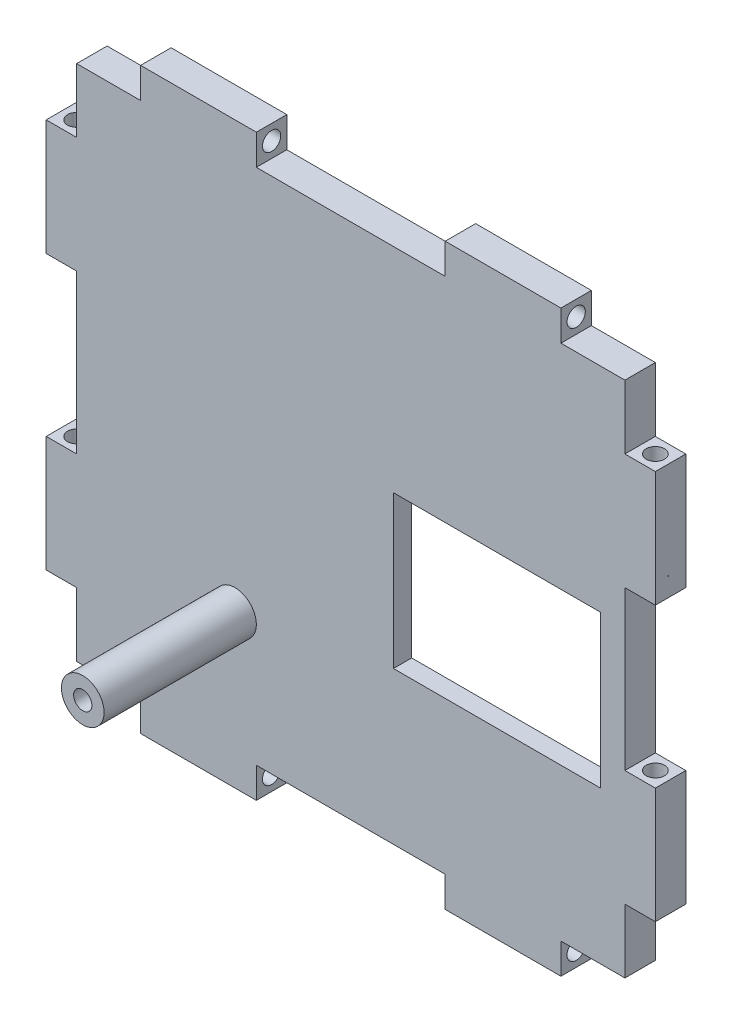
SolidWorks part; units mm, degrees
material "Alliage 1060"
ref_plane "Plan de dessus" through (0, 0, 0) normal (0, 0, 1) x (1, 0, 0)
ref_plane "Plan de droite" through (0, 0, 0) normal (0, 1, 0) x (1, 0, 0)
ref_plane "Plan de face" through (0, 0, 0) normal (1, 0, 0) x (0, 0, -1)
sketch "Esquisse1" plane through (0, 0, 0) normal (0, 0, 1) x (1, 0, 0)
  line L6 (15.5, 95.5) -> (15.5, 90.5)
  line L8 (34.5, 95.5) -> (34.5, 90.5)
  line L10 (65.5, 95.5) -> (65.5, 90.5)
  line L12 (84.5, 95.5) -> (84.5, 90.5)
  line L13 (100, 80) -> (95, 80)
  line L15 (100, 61) -> (95, 61)
  line L17 (100, 35) -> (95, 35)
  line L19 (100, 16) -> (95, 16)
  line L22 (84.5, 0.5) -> (84.5, 5.5)
  line L24 (65.5, 0.5) -> (65.5, 5.5)
  line L26 (34.5, 0.5) -> (34.5, 5.5)
  line L28 (15.5, 0.5) -> (15.5, 5.5)
  line L29 (0, 16) -> (5, 16)
  line L31 (0, 35) -> (5, 35)
  line L33 (0, 61) -> (5, 61)
  line L35 (0, 80) -> (5, 80)
  line L44 (5, 80) -> (5, 90.5)
  line L45 (0, 80) -> (0, 61)
  line L46 (5, 61) -> (5, 35)
  line L47 (0, 35) -> (0, 16)
  line L48 (5, 16) -> (5, 5.5)
  line L49 (15.5, 5.5) -> (5, 5.5)
  line L50 (34.5, 5.5) -> (65.5, 5.5)
  line L51 (84.5, 5.5) -> (95, 5.5)
  line L52 (84.5, 0.5) -> (65.5, 0.5)
  line L53 (34.5, 0.5) -> (15.5, 0.5)
  line L54 (95, 5.5) -> (95, 16)
  line L55 (100, 16) -> (100, 35)
  line L56 (95, 61) -> (95, 35)
  line L57 (100, 80) -> (100, 61)
  line L58 (95, 90.5) -> (95, 80)
  line L59 (15.5, 95.5) -> (34.5, 95.5)
  line L60 (65.5, 95.5) -> (84.5, 95.5)
  line L61 (34.5, 90.5) -> (65.5, 90.5)
  line L62 (15.5, 90.5) -> (5, 90.5)
  line L63 (84.5, 90.5) -> (95, 90.5)
  dimension "D1" = 10.5
  dimension "D2" = 19
  dimension "D3" = 19
  dimension "D4" = 5
  dimension "D5" = 10.5
  dimension "D6" = 26
  dimension "D7" = 19
  dimension "D8" = 19
  dimension "D9" = 10.5
  dimension "D10" = 19
  dimension "D11" = 19
  dimension "D12" = 10.5
  dimension "D13" = 26
  dimension "D14" = 10.5
  dimension "D15" = 10.5
  dimension "D16" = 31
  dimension "D17" = 10.5
  dimension "D18" = 19
  dimension "D19" = 19
  dimension "D20" = 10.5
  dimension "D21" = 31
extrude "Boss.-Extru.1" add sketch "Esquisse1" along normal blind 5
sketch "Esquisse2" plane through (0, 16, 0) normal (0, -1, 0) x (1, 0, 0)
  line L0 (100, 5) -> (100, 0) construction
  line L2 (95, 0) -> (100, 0) construction
  circle A0 centre (97.5, 2.5) radius 1.5
  dimension "D1" = 3
  dimension "D2" = 2.5
  dimension "D3" = 2.5
extrude "Enlèv. mat.-Extru.1" cut sketch "Esquisse2" against normal up to surface (64 mm away) up to face at (97.5, 80, 2.5)
sketch "Esquisse3" plane through (95, 0, 0) normal (1, 0, 0) x (0, 0, -1)
  line L2 (0, 80) -> (0, 90.5) construction
  line L3 (-5, 95.5) -> (0, 95.5) construction
  circle A0 centre (-2.5, 93) radius 1.5
  dimension "D1" = 3
  dimension "D2" = 2.5
  dimension "D3" = 2.5
extrude "Enlèv. mat.-Extru.2" cut sketch "Esquisse3" against normal up to surface (90 mm away) up to face at (5, 85.25, 2.5)
sketch "Esquisse4" plane through (0, 80, 0) normal (0, 1, 0) x (1, 0, 0)
  line L0 (5, 0) -> (0, 0) construction
  line L1 (0, -5) -> (0, 0) construction
  circle A0 centre (2.5, -2.5) radius 1.5
  dimension "D1" = 3
  dimension "D2" = 2.5
  dimension "D3" = 2.5
extrude "Enlèv. mat.-Extru.3" cut sketch "Esquisse4" against normal up to surface (64 mm away) up to face at (2.5, 16, 2.5)
sketch "Esquisse5" plane through (15.5, 0, 0) normal (-1, 0, 0) x (0, 0, 1)
  line L0 (5, 5.5) -> (5, 0.5) construction
  line L1 (5, 0.5) -> (0, 0.5) construction
  circle A0 centre (2.5, 3) radius 1.5
  dimension "D1" = 3
  dimension "D2" = 2.5
  dimension "D3" = 2.5
extrude "Enlèv. mat.-Extru.4" cut sketch "Esquisse5" against normal up to surface (69 mm away) up to face at (84.5, 3, 2.5)
sketch "Esquisse6" plane through (0, 0, 0) normal (0, 0, -1) x (-1, 0, 0)
  line L0 (0, 35) -> (0, 16) construction
  line L3 (-15.5, 0.5) -> (-34.5, 0.5) construction
  circle A0 centre (-31, 25.5) radius 3.5
  circle A1 centre (-31, 25.5) radius 1.5
  dimension "D1" = 31
  dimension "D3" = 7
  dimension "D4" = 3
  dimension "D2" = 25
extrude "Boss.-Extru.2" add sketch "Esquisse6" against normal blind 30
sketch "Esquisse7" plane through (0, 0, 5) normal (0, 0, 1) x (1, 0, 0)
  circle A0 centre (31, 25.5) radius 1.5
extrude "Enlèv. mat.-Extru.5" cut sketch "Esquisse7" against normal up to next
sketch "Esquisse8" plane through (0, 0, 0) normal (0, 0, -1) x (-1, 0, 0)
  line L6 (-91, 55.5) -> (-57, 55.5)
  line L7 (-57, 55.5) -> (-57, 30.5)
  line L8 (-91, 30.5) -> (-57, 30.5)
  line L9 (-91, 55.5) -> (-91, 30.5)
  line L10 (-34.5, 5.5) -> (-65.5, 5.5) construction
  line L11 (-95, 35) -> (-95, 61) construction
  dimension "D1" = 25
  dimension "D2" = 25
  dimension "D3" = 34
  dimension "D4" = 4
extrude "Enlèv. mat.-Extru.6" cut sketch "Esquisse8" against normal up to surface (5 mm away) contours L6 L7 L8 L9 up to face at (27.5, 25.5, 5)
sketch "Esquisse9" plane through (0, 0, 0) normal (0, 0, -1) x (-1, 0, 0)
  line L1 (-91, 68.5) -> (-40, 68.5)
  line L2 (-91, 68.5) -> (-91, 17.5)
  line L3 (-91, 17.5) -> (-40, 17.5)
  line L4 (-40, 68.5) -> (-40, 17.5)
  line L6 (-91, 55.5) -> (-91, 30.5) construction
  line L7 (-63.3417, 55.5) -> (-63.3417, 68.5) construction
  line L8 (-91, 55.5) -> (-57, 55.5) construction
  line L9 (-63.3417, 30.5) -> (-63.3417, 17.5) construction
  line L10 (-91, 30.5) -> (-57, 30.5) construction
  dimension "D1" = 51
  dimension "D2" = 51
extrude "Enlèv. mat.-Extru.7" cut sketch "Esquisse9" against normal blind 2
